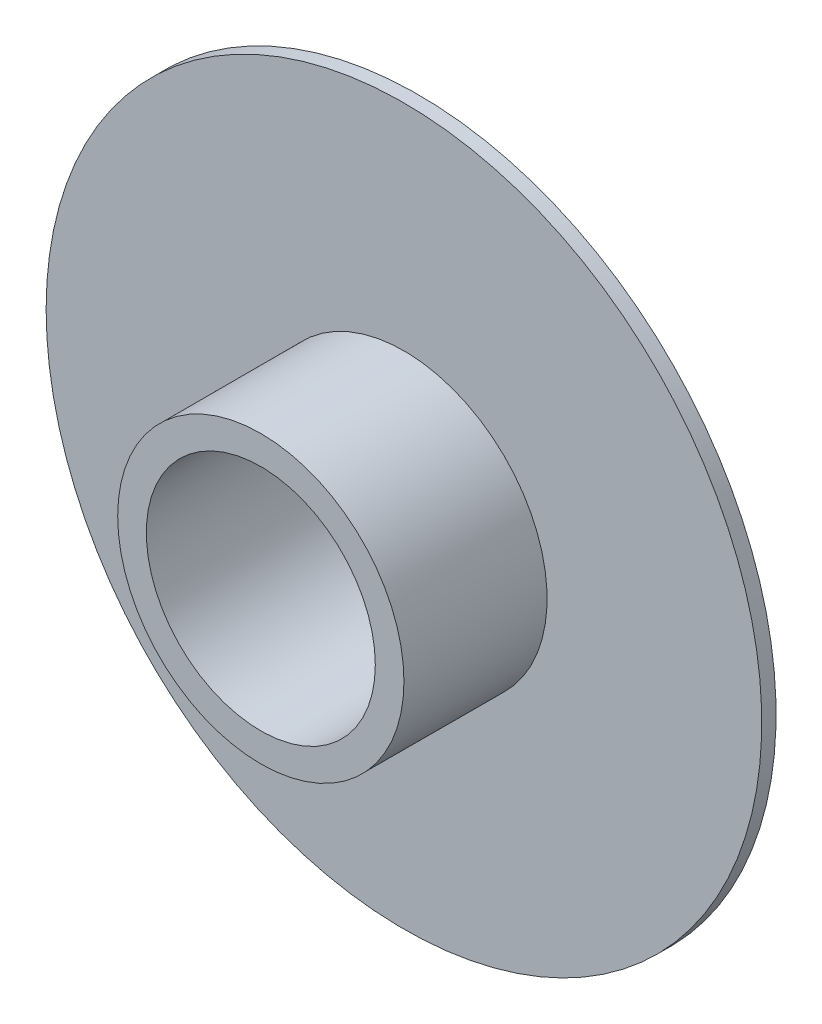
SolidWorks part; units mm, degrees
ref_plane "Front Plane" through (0, 0, 0) normal (0, 0, 1) x (1, 0, 0)
ref_plane "Top Plane" through (0, 0, 0) normal (0, 1, 0) x (1, 0, 0)
ref_plane "Right Plane" through (0, 0, 0) normal (1, 0, 0) x (0, 0, -1)
sketch "Sketch1" plane through (0, 0, 0) normal (0, 0, 1) x (1, 0, 0)
  circle A0 centre (0, 0) radius 4
  circle A1 centre (0, 0) radius 5
  dimension "D1" = 8
  dimension "D2" = 10
extrude "Boss-Extrude1" add sketch "Sketch1" along normal mid plane 6
ref_plane "Plane1" through (0, 0, -2.5) normal (0, 0, -1) x (-1, 0, 0)
sketch "Sketch2" plane through (0, 0, -2.5) normal (0, 0, -1) x (-1, 0, 0)
  circle A0 centre (0, 0) radius 5
  circle A1 centre (0, 0) radius 12.5
  dimension "D1" = 10
  dimension "D2" = 25
extrude "Boss-Extrude2" add sketch "Sketch2" against normal blind 0.5
